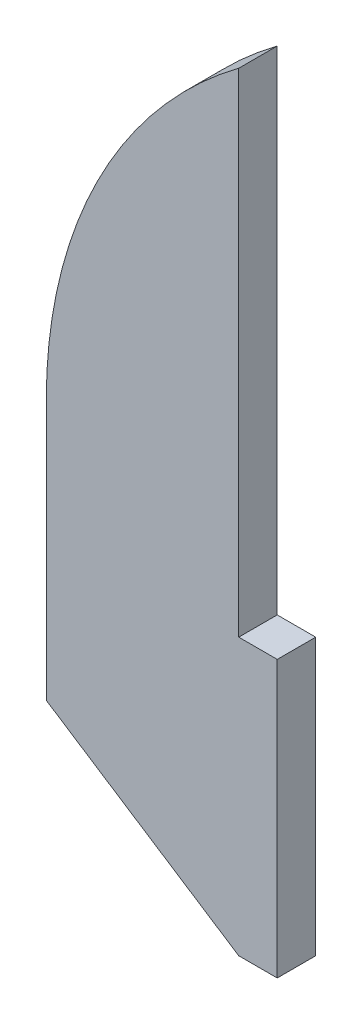
SolidWorks part; units mm, degrees
ref_plane "Front Plane" through (0, 0, 0) normal (0, 0, 1) x (1, 0, 0)
ref_plane "Top Plane" through (0, 0, 0) normal (0, 1, 0) x (1, 0, 0)
ref_plane "Right Plane" through (0, 0, 0) normal (1, 0, 0) x (0, 0, -1)
sketch "Sketch1" plane through (0, 0, 0) normal (0, 0, 1) x (1, 0, 0)
  line L0 (12.5, -45) -> (-12.5, -28.7648)
  line L1 (12.5, -45) -> (-12.5, -45)
  line L2 (12.5, -45) -> (12.5, -44.8433)
  line L3 (12.5, -9.1567) -> (12.5, 54.8433)
  line L4 (-12.5, -45) -> (-12.5, 5)
  line L5 (-12.5, 45) -> (12.5, -45) construction
  line L6 (12.5, -45) -> (17.5, -45)
  line L7 (12.5, -45) -> (12.5, -44.8433)
  line L8 (12.5, -9.1567) -> (17.5, -9.1567)
  line L9 (17.5, -45) -> (17.5, -9.1567)
  arc A0 (12.5, 54.8433) -> (-12.5, 5) centre (49.687, 5) ccw
  arc A1 (15.8176, -47.1544) -> (12.5, -44.8433) centre (49.687, 5) ccw
  point P13 (0, 0)
  dimension "D1" = 25
  dimension "D2" = 90
  dimension "D3" = 33
  dimension "D4" = 5
  dimension "D5" = 64
  dimension "D6" = 50
extrude "Boss-Extrude1" add sketch "Sketch1" along normal blind 5 contours A0 L5 A1 L2 L6 L9 L8 L3 | L5 A0 L4 L0 A1 | L5 A1 L4 L0 | A1 L5 L2
